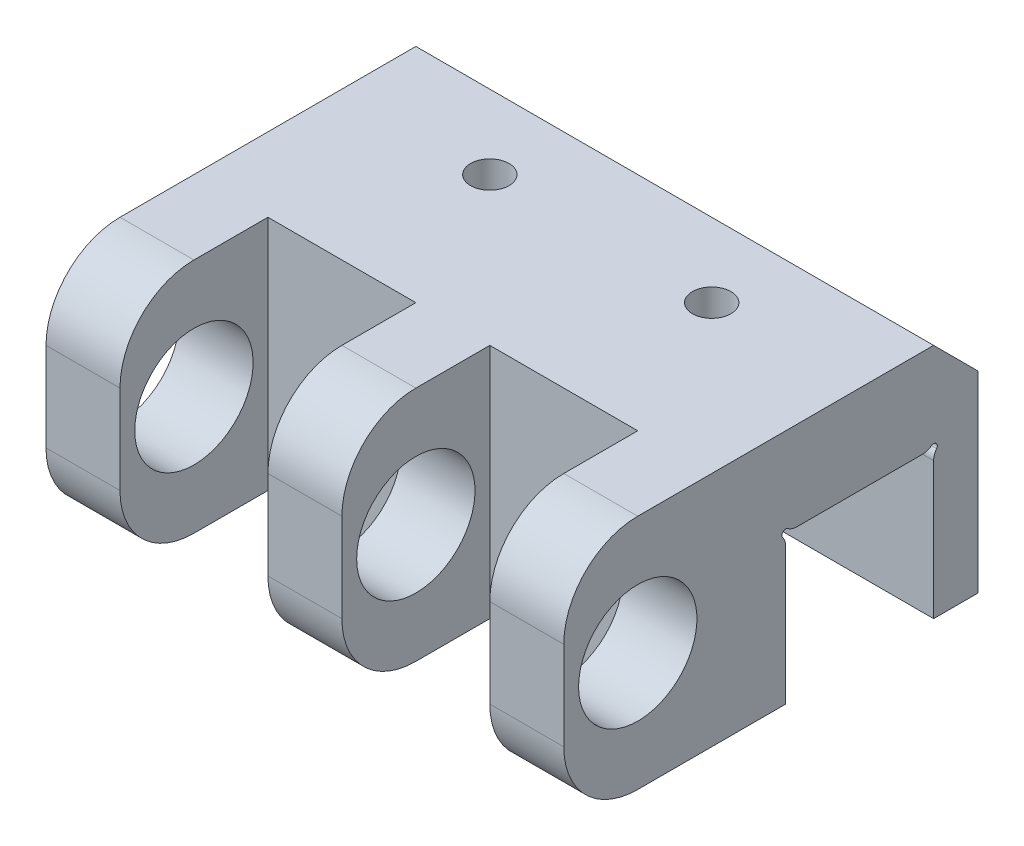
SolidWorks part; units mm, degrees
ref_plane "Płaszczyzna przednia" through (0, 0, 0) normal (0, 0, 1) x (1, 0, 0)
ref_plane "Płaszczyzna górna" through (0, 0, 0) normal (0, 1, 0) x (1, 0, 0)
ref_plane "Płaszczyzna prawa" through (0, 0, 0) normal (1, 0, 0) x (0, 0, -1)
sketch "Szkic1" plane through (0, 0, 0) normal (0, 0, 1) x (1, 0, 0)
  line L1 (0, 0) -> (70, 0)
  line L2 (0, 0) -> (0, 32)
  line L3 (0, 32) -> (70, 32)
  line L4 (70, 0) -> (70, 32)
  dimension "D1" = 70
  dimension "D2" = 32
extrude "Dodanie-wyciągnięcie1" add sketch "Szkic1" along normal blind 10
sketch "Szkic2" plane through (0, 0, 10) normal (0, 0, 1) x (1, 0, 0)
  line L0 (0, 0) -> (70, 0) construction
  line L1 (0, 32) -> (10, 32)
  line L2 (0, 32) -> (0, 0)
  line L3 (0, 0) -> (10, 0)
  line L4 (10, 32) -> (10, 0)
  line L5 (70, 32) -> (0, 32) construction
  line L6 (30, 0) -> (40, 0)
  line L7 (30, 0) -> (30, 32)
  line L8 (30, 32) -> (40, 32)
  line L9 (40, 0) -> (40, 32)
  line L11 (70, 32) -> (60, 32)
  line L12 (70, 32) -> (70, 0)
  line L13 (70, 0) -> (60, 0)
  line L14 (60, 32) -> (60, 0)
  dimension "D1" = 10
  dimension "D2" = 10
  dimension "D3" = 10
  dimension "D4" = 20
extrude "Dodanie-wyciągnięcie2" add sketch "Szkic2" along normal blind 20
sketch "Szkic3" plane through (0, 0, 0) normal (0, 0, -1) x (-1, 0, 0)
  line L0 (0, 32) -> (0, 0) construction
  line L1 (-70, 32) -> (0, 32)
  line L2 (-70, 32) -> (-70, 20)
  line L3 (-70, 20) -> (0, 20)
  line L4 (0, 32) -> (0, 20)
  dimension "D1" = 12
extrude "Dodanie-wyciągnięcie3" add sketch "Szkic3" along normal blind 26
sketch "Szkic4" plane through (0, 20, 0) normal (0, -1, 0) x (1, 0, 0)
  line L0 (70, -26) -> (70, 0) construction
  line L1 (0, -26) -> (70, -26)
  line L2 (0, -26) -> (0, -20)
  line L3 (0, -20) -> (70, -20)
  line L4 (70, -26) -> (70, -20)
  line L5 (0, 0) -> (70, 0) construction
  dimension "D1" = 20
extrude "Dodanie-wyciągnięcie4" add sketch "Szkic4" along normal blind 20
sketch "Szkic5" plane through (0, 0, 0) normal (-1, 0, 0) x (0, 0, 1)
  circle A0 centre (-20, 20) radius 0.5
  circle A1 centre (0, 20) radius 0.5
  dimension "D1" = 1
extrude "Wytnij-wyciągnięcie1" cut sketch "Szkic5" against normal through all
fillet "Zaokrąglenie1" radius 2 4 edges at (35, 19.5, 0) (35, 20, -0.5) (35, 20, -19.5) (35, 19.5, -20)
sketch "Szkic6" plane through (0, 0, 0) normal (-1, 0, 0) x (0, 0, 1)
  line L4 (10, 32) -> (10, 0)
  line L5 (10, 0) -> (30, 0)
  line L6 (30, 0) -> (30, 32)
  line L7 (30, 32) -> (10, 32)
  line L8 (10, 32) -> (10, 0)
  line L9 (10, 0) -> (30, 0)
  line L10 (30, 0) -> (30, 32)
  line L11 (30, 32) -> (10, 32)
  circle A0 centre (20, 16) radius 8
  point P6 (0, 0)
  dimension "D4" = 16
  dimension "D2" = 16
  dimension "D3" = 10
  dimension "D1" = 0
extrude "Wytnij-wyciągnięcie2" cut sketch "Szkic6" against normal through all contours A0
fillet "Zaokrąglenie2" radius 10 6 edges at (5, 0, 30) (35, 0, 30) (65, 0, 30) (65, 32, 30) (35, 32, 30) (5, 32, 30)
sketch "Szkic7" plane through (0, 20, 0) normal (0, -1, 0) x (1, 0, 0)
  line L0 (0, 0) -> (70, 0) construction
  line L1 (0, -18.5) -> (0, -1.5) construction
  line L2 (70, -18.5) -> (70, -1.5) construction
  circle A0 centre (20, -10) radius 2.6
  circle A1 centre (50, -10) radius 2.6
  point P4 (0, 0)
  dimension "D1" = 5.2
  dimension "D2" = 10
  dimension "D3" = 20
  dimension "D4" = 20
extrude "Wytnij-wyciągnięcie3" cut sketch "Szkic7" against normal through all
sketch "Szkic8" plane through (0, 0, -26) normal (0, 0, -1) x (-1, 0, 0)
  line L0 (0, 0) -> (0, 32) construction
  line L3 (0, 0) -> (-70, 0) construction
  circle A0 centre (-35, 10) radius 2.6
  point P2 (0, 0)
  dimension "D1" = 5.2
  dimension "D3" = 10
  dimension "D2" = 35
extrude "Wytnij-wyciągnięcie4" cut sketch "Szkic8" against normal blind 20
chamfer "Sfazowanie1" distance 6 angle 45 1 edges at (35, 32, -26)
